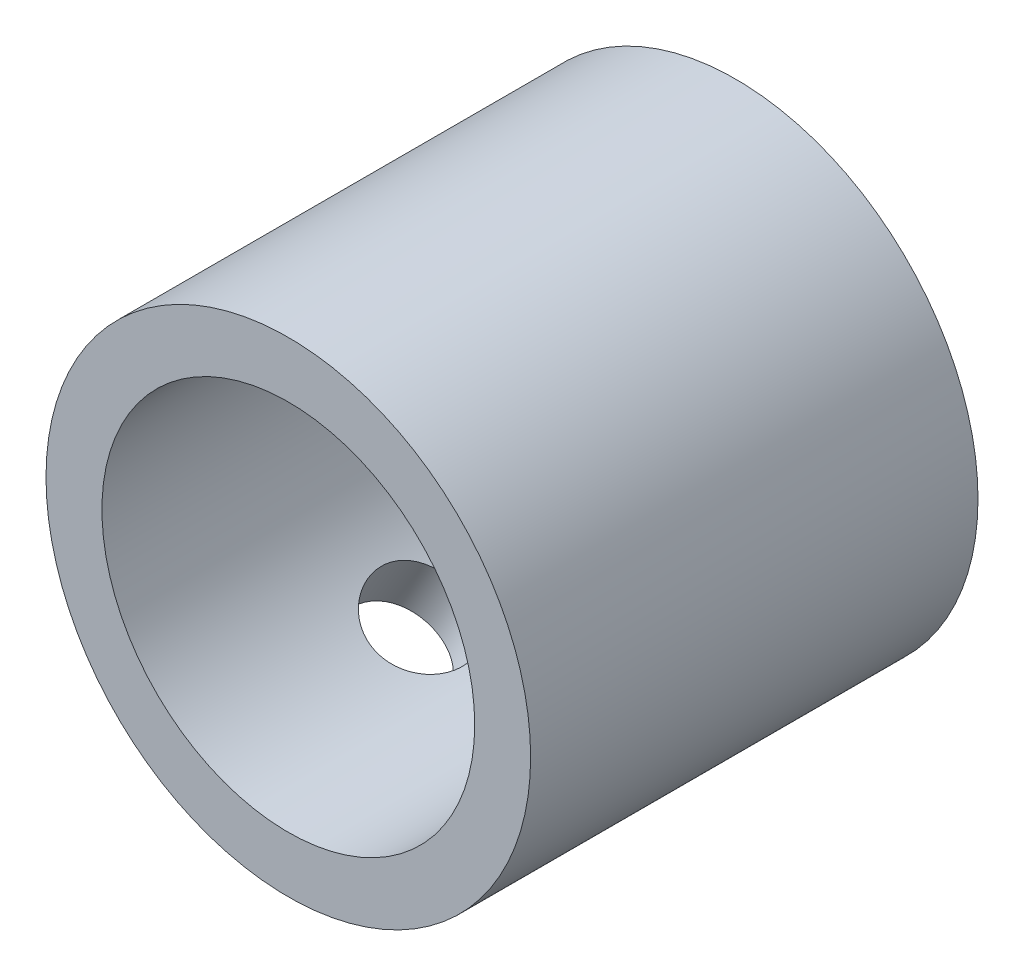
SolidWorks part; units mm, degrees
ref_plane "Front Plane" through (0, 0, 0) normal (0, 0, 1) x (1, 0, 0)
ref_plane "Top Plane" through (0, 0, 0) normal (0, 1, 0) x (1, 0, 0)
ref_plane "Right Plane" through (0, 0, 0) normal (1, 0, 0) x (0, 0, -1)
sketch "Sketch1" plane through (0, 0, 0) normal (0, 0, 1) x (1, 0, 0)
  circle A0 centre (0, 0) radius 6.5
  circle A1 centre (0, 0) radius 5
  dimension "D1" = 10
  dimension "D2" = 13
extrude "Boss-Extrude1" add sketch "Sketch1" along normal mid plane 12
sketch "Sketch3" plane through (0, 0, 0) normal (0, 0, 1) x (1, 0, 0)
  line L1 (-1.2725, -2.204) -> (-3.7989, -6.5799)
  line L2 (-3.7989, -6.5799) -> (-4.8814, -5.9549)
  line L3 (-4.8814, -5.9549) -> (-2.355, -1.579)
  line L4 (-2.355, -1.579) -> (-1.2725, -2.204)
revolve "Cut-Revolve1" cut sketch "Sketch3" angle 360 about L1
